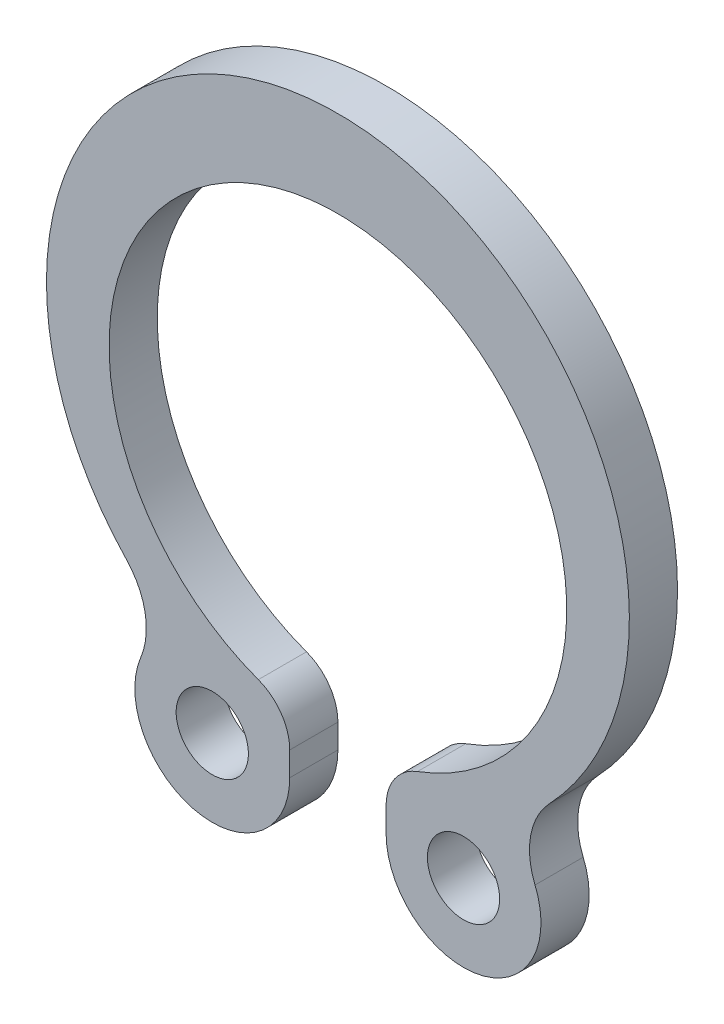
SolidWorks part; units mm, degrees
material "Сталь 65Г ГОСТ 14959-79"
ref_plane "Спереди" through (0, 0, 0) normal (0, 0, 1) x (1, 0, 0)
ref_plane "Сверху" through (0, 0, 0) normal (0, 1, 0) x (1, 0, 0)
ref_plane "Справа" through (0, 0, 0) normal (1, 0, 0) x (0, 0, -1)
sketch "Эскиз10-165" plane through (0, 0, 0) normal (0, 0, 1) x (1, 0, 0)
  line L0 (0, 0) -> (0, -5.891) construction
  line L1 (-1, -5.391) -> (-1, -5.891)
  line L3 (1, -5.391) -> (1, -5.891)
  arc A0 (1.6522, -4.4534) -> (-1.6522, -4.4534) centre (0, 0) ccw
  arc A1 (4.3887, -3.6644) -> (-4.3887, -3.6644) centre (0, 0.5) ccw
  arc A2 (-4.0919, -5.2732) -> (-4.3887, -3.6644) centre (-5.4768, -4.6969) ccw
  arc A3 (-1, -5.391) -> (-1.6522, -4.4534) centre (-2, -5.391) ccw
  circle A4 centre (-2.6077, -5.891) radius 0.75
  arc A5 (-1, -5.891) -> (-4.0919, -5.2732) centre (-2.6077, -5.891) cw
  arc A6 (1, -5.891) -> (4.0919, -5.2732) centre (2.6077, -5.891) ccw
  circle A7 centre (2.6077, -5.891) radius 0.75
  arc A8 (1, -5.391) -> (1.6522, -4.4534) centre (2, -5.391) cw
  arc A9 (4.0919, -5.2732) -> (4.3887, -3.6644) centre (5.4768, -4.6969) cw
  circle A10 centre (0, 0) radius 8.8 construction
  circle A11 centre (0, 0) radius 5 construction
  dimension "d2" = 9.5
  dimension "d3" = 12.1
  dimension "r2" = 1
  dimension "D5" = 0.5
  dimension "d4" = 1.5
  dimension "r1" = 1.5
  dimension "D" = 17.6
  dimension "dval" = 10
  dimension "b" = 1.8
  dimension "a" = 3.3
  dimension "l" = 2
extrude "Бобышка10-165" add sketch "Эскиз10-165" along normal blind 1
sketch "Эскиз170-200" [suppressed] plane through (0, 0, 0) normal (0, 0, 1) x (1, 0, 0)
  line L0 (0, 0) -> (0, -107.5) construction
  line L1 (-4, -97.4179) -> (-4, -107.4269)
  line L2 (4, -97.4179) -> (4, -107.4269)
  line L3 (-7.6095, -97.2026) -> (-8.3905, -107.1781) construction
  arc A0 (4, -97.4179) -> (-4, -97.4179) centre (0, 0) ccw
  arc A1 (4, -107.4269) -> (-4, -107.4269) centre (0, 2) ccw
  circle A2 centre (0, 0) radius 114.5 construction
  circle A3 centre (-8, -102.1903) radius 2
  circle A4 centre (8, -102.1903) radius 2
  circle A5 centre (0, 0) radius 100 construction
  circle A6 centre (0, 0) radius 100 construction
  circle A7 centre (0, 0) radius 114.5 construction
  dimension "D1" = 4
  dimension "d2" = 162
  dimension "d3" = 181.6
  dimension "d4" = 4
  dimension "D5" = 200
  dimension "D6" = 229
  dimension "b" = 12.9
  dimension "l" = 8
extrude "Бобышка170-200" [suppressed] add sketch "Эскиз170-200" along normal blind 3
sketch "Эскиз4-9" plane through (0, 0, 0) normal (0, 0, 1) x (1, 0, 0)
  line L0 (0, 0) -> (0, -2.7771) construction
  line L1 (-0.5, -1.6771) -> (-0.5, -2.2771)
  line L2 (-0.5, -3.2771) -> (-0.5, -3.8771)
  line L3 (0.5, -1.6771) -> (0.5, -2.2771)
  line L4 (0.5, -3.2771) -> (0.5, -3.8771)
  circle A0 centre (0, 0) radius 2 construction
  circle A1 centre (0, 0) radius 4.4 construction
  arc A2 (0.5, -1.6771) -> (-0.5, -1.6771) centre (0, 0) ccw
  arc A3 (1.9286, -1.3891) -> (-1.9286, -1.3891) centre (0, 0.17) ccw
  arc A4 (-0.5, -2.2771) -> (-0.5, -3.2771) centre (-0.5, -2.7771) ccw
  arc A5 (-0.5, -3.8771) -> (-1.5889, -2.6214) centre (-0.5, -2.7771) cw
  arc A6 (-1.5889, -2.6214) -> (-1.9286, -1.3891) centre (-3.1728, -2.3951) ccw
  arc A7 (0.5, -2.2771) -> (0.5, -3.2771) centre (0.5, -2.7771) cw
  arc A8 (0.5, -3.8771) -> (1.5889, -2.6214) centre (0.5, -2.7771) ccw
  arc A9 (1.5889, -2.6214) -> (1.9286, -1.3891) centre (3.1728, -2.3951) cw
  dimension "dval" = 4
  dimension "D" = 8.8
  dimension "d2" = 3.5
  dimension "d3" = 4.96
  dimension "d4" = 1
  dimension "r1" = 1.6
  dimension "b" = 0.9
  dimension "a" = 2.2
extrude "Бобышка-4-9" [suppressed] add sketch "Эскиз4-9" along normal blind 0.4 separate body
